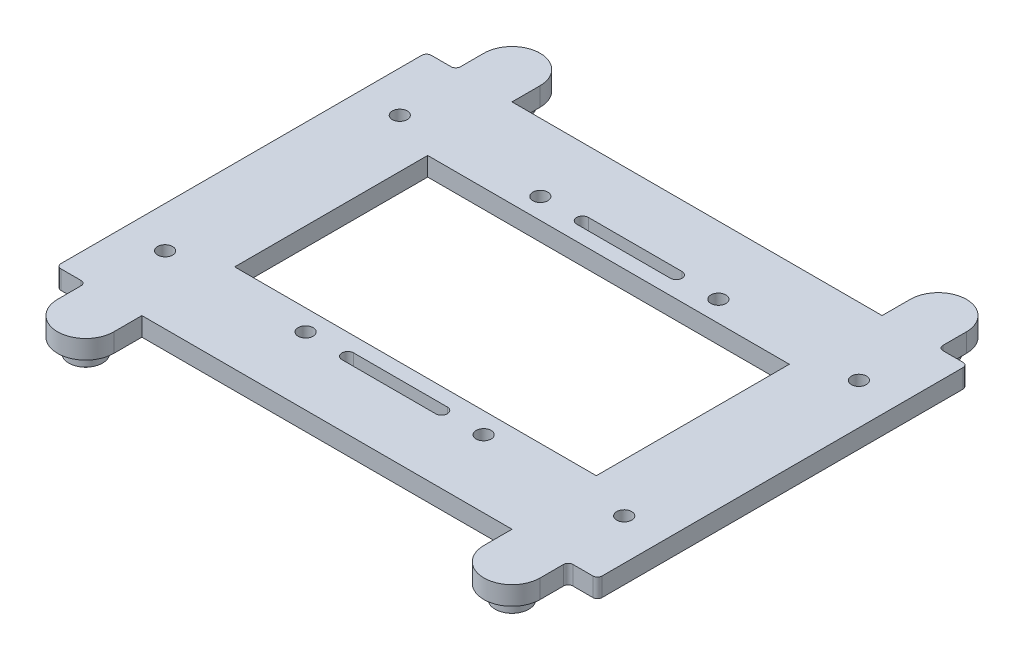
SolidWorks part; units mm, degrees
ref_plane "前视基准面" through (0, 0, 0) normal (0, 0, 1) x (1, 0, 0)
ref_plane "上视基准面" through (0, 0, 0) normal (0, 1, 0) x (1, 0, 0)
ref_plane "右视基准面" through (0, 0, 0) normal (1, 0, 0) x (0, 0, -1)
other "Configuration Table"
sketch "草图1" plane through (0, 0, 0) normal (0, 1, 0) x (1, 0, 0)
  line L0 (-39.5, -39.5) -> (39.5, -39.5)
  line L1 (-57.75, 39.5) -> (-51.5, 39.5)
  line L2 (-57.75, 39.5) -> (-57.75, -39.5)
  line L3 (-57.75, -39.5) -> (-51.5, -39.5)
  line L4 (57.75, 39.5) -> (57.75, -39.5)
  line L5 (-57.75, 39.5) -> (57.75, -39.5) construction
  line L6 (-57.75, -39.5) -> (57.75, 39.5) construction
  line L9 (-51.5, 39.5) -> (-51.5, 45.5)
  line L11 (-39.5, 39.5) -> (-39.5, 45.5)
  line L12 (39.5, 39.5) -> (39.5, 45.5)
  line L14 (51.5, 39.5) -> (51.5, 45.5)
  line L15 (-78.7463, 0) -> (58.6748, 0) construction
  line L16 (51.5, -39.5) -> (51.5, -45.5)
  line L18 (39.5, -39.5) -> (39.5, -45.5)
  line L21 (-39.5, -39.5) -> (-39.5, -45.5)
  line L23 (-51.5, -39.5) -> (-51.5, -45.5)
  line L25 (51.5, 39.5) -> (57.75, 39.5)
  line L26 (51.5, -39.5) -> (57.75, -39.5)
  line L50 (-51.5, 45.5) -> (-39.5, 45.5) construction
  line L53 (-39.5, 39.5) -> (39.5, 39.5)
  arc A16 (-39.5, 45.5) -> (-51.5, 45.5) centre (-45.5, 45.5) ccw
  arc A17 (39.5, 45.5) -> (51.5, 45.5) centre (45.5, 45.5) cw
  arc A18 (39.5, -45.5) -> (51.5, -45.5) centre (45.5, -45.5) ccw
  arc A19 (-39.5, -45.5) -> (-51.5, -45.5) centre (-45.5, -45.5) cw
  point P0 (0, 0)
  dimension "D10" = 91
  dimension "D1" = 115.5
  dimension "D2" = 45.5
  dimension "D3" = 45.5
  dimension "D4" = 12
  dimension "D5" = 6
extrude "凸台-拉伸1" add sketch "草图1" against normal blind 4
sketch "草图3" plane through (0, -4, 0) normal (0, -1, 0) x (1, 0, 0)
  line L0 (57.75, 39.5) -> (57.75, -39.5) construction
  line L1 (-55.25, -27) -> (55.25, -27)
  line L2 (-55.25, -27) -> (-55.25, 27)
  line L3 (-55.25, 27) -> (55.25, 27)
  line L4 (55.25, -27) -> (55.25, 27)
  line L5 (-55.25, -27) -> (55.25, 27) construction
  line L6 (-55.25, 27) -> (55.25, -27) construction
  point P0 (0, 0)
  dimension "D1" = 2.5
sketch "草图4" plane through (0, -4, 0) normal (0, -1, 0) x (1, 0, 0)
  line L1 (-71.7869, 0) -> (71.1524, 0) construction
  line L2 (0, 61.1393) -> (0, -47.8922) construction
  circle A4 centre (-45.5, 45.5) radius 3.6
  circle A5 centre (-45.5, -45.5) radius 3.6
  circle A6 centre (45.5, -45.5) radius 3.6
  circle A7 centre (45.5, 45.5) radius 3.6
extrude "凸台-拉伸2" add sketch "草图4" along normal blind 3 separate body
sketch "草图5" plane through (0, -7, 0) normal (0, -1, 0) x (1, 0, 0)
  line L0 (-58.868, 0) -> (56.1189, 0) construction
  line L1 (0, 46.5823) -> (0, -51.4835) construction
  circle A0 centre (-45.5, 45.5) radius 1.8
  circle A4 centre (-45.5, -45.5) radius 1.8
  circle A5 centre (45.5, -45.5) radius 1.8
  circle A6 centre (45.5, 45.5) radius 1.8
extrude "凸台-拉伸3" add sketch "草图5" along normal blind 1.3 separate body
sketch "草图6" plane through (0, -4, 0) normal (0, -1, 0) x (1, 0, 0)
  line L1 (-47.5, 29.5) -> (47.5, 29.5)
  line L2 (-47.5, 29.5) -> (-47.5, -29.5)
  line L3 (-47.5, -29.5) -> (47.5, -29.5)
  line L4 (47.5, 29.5) -> (47.5, -29.5)
sketch "草图10" plane through (0, 0, 0) normal (0, 1, 0) x (1, 0, 0)
  line L5 (38.6, 20.6) -> (-38.6, 20.6)
  line L6 (38.6, 20.6) -> (38.6, -20.6)
  line L7 (38.6, -20.6) -> (-38.6, -20.6)
  line L8 (-38.6, 20.6) -> (-38.6, -20.6)
  line L9 (38.6, 20.6) -> (-38.6, -20.6) construction
  line L10 (38.6, -20.6) -> (-38.6, 20.6) construction
  point P0 (0, 0)
  dimension "D1" = 77.2
  dimension "D2" = 41.2
extrude "切除-拉伸5" cut sketch "草图10" against normal through all
sketch "草图16" plane through (0, 0, 0) normal (0, 1, 0) x (1, 0, 0)
  line L0 (-10, 25.05) -> (10, 25.05) construction
  line L1 (-10, 26.3) -> (10, 26.3)
  line L2 (-10, 23.8) -> (10, 23.8)
  line L3 (-1000, 0) -> (49000, 0) construction
  line L4 (0, -1000) -> (0, 49000) construction
  line L6 (-10, -25.05) -> (10, -25.05) construction
  line L7 (-10, -26.3) -> (10, -26.3)
  line L8 (-10, -23.8) -> (10, -23.8)
  line L9 (38.6, 20.6) -> (-38.6, 20.6) construction
  arc A0 (-10, 26.3) -> (-10, 23.8) centre (-10, 25.05) ccw
  arc A1 (10, 23.8) -> (10, 26.3) centre (10, 25.05) ccw
  arc A2 (-10, -26.3) -> (-10, -23.8) centre (-10, -25.05) cw
  arc A3 (10, -23.8) -> (10, -26.3) centre (10, -25.05) cw
  circle A4 centre (19, 25.05) radius 1.6
  circle A5 centre (49, 25.05) radius 1.6
  circle A6 centre (-49, 25.05) radius 1.6
  circle A7 centre (-19, 25.05) radius 1.6
  circle A8 centre (49, -25.05) radius 1.6
  circle A9 centre (19, -25.05) radius 1.6
  circle A10 centre (-19, -25.05) radius 1.6
  circle A11 centre (-49, -25.05) radius 1.6
  point P2 (0, 25.05)
  point P17 (0, -25.05)
  dimension "D4" = 3.2
  dimension "D5" = 3.2
  dimension "D3" = 4.45
  dimension "D1" = 2.5
  dimension "D2" = 20
  dimension "D6" = 4.45
  dimension "D7" = 9
  dimension "D8" = 30
extrude "切除-拉伸6" cut sketch "草图16" against normal blind 10
fillet "圆角1" radius 1 8 edges at (-51.5, -2, -39.5) (51.5, -2, -39.5) (51.5, -2, 39.5) (-51.5, -2, 39.5) (-57.75, -2, 39.5) (-57.75, -2, -39.5) (57.75, -2, 39.5) (57.75, -2, -39.5)
